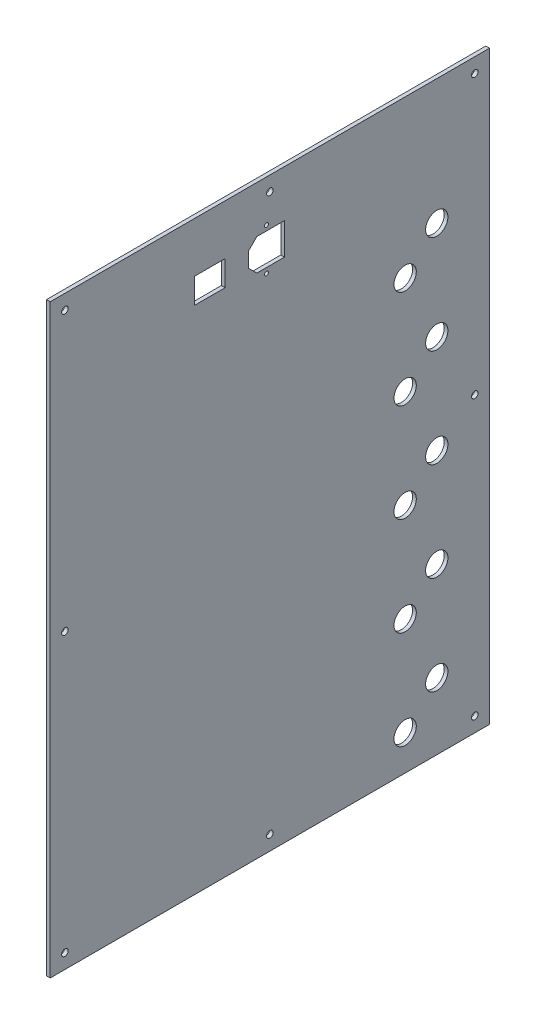
SolidWorks part; units mm, degrees
ref_plane "Front Plane" through (0, 0, 0) normal (1, 0, 0) x (0, 1, 0)
ref_plane "Top Plane" through (0, 0, 0) normal (0, 0, 1) x (0, 1, 0)
ref_plane "Right Plane" through (0, 0, 0) normal (0, 1, 0) x (-1, 0, 0)
sketch "Sketch1" plane through (0, 0, 0) normal (1, 0, 0) x (0, 1, 0)
  line L1 (-250, -187.5) -> (250, -187.5)
  line L2 (-250, -187.5) -> (-250, 187.5)
  line L3 (-250, 187.5) -> (250, 187.5)
  line L4 (250, -187.5) -> (250, 187.5)
  line L5 (-250, -187.5) -> (250, 187.5) construction
  line L6 (-250, 187.5) -> (250, -187.5) construction
  line L7 (237.5, -175) -> (-237.5, -175) construction
  line L8 (237.5, -175) -> (237.5, 175) construction
  line L9 (237.5, 175) -> (-237.5, 175) construction
  line L10 (-237.5, -175) -> (-237.5, 175) construction
  line L11 (237.5, -175) -> (-237.5, 175) construction
  line L12 (237.5, 175) -> (-237.5, -175) construction
  circle A0 centre (-237.5, 175) radius 2.8
  circle A1 centre (237.5, 175) radius 2.8
  circle A2 centre (237.5, -175) radius 2.8
  circle A3 centre (-237.5, -175) radius 2.8
  circle A4 centre (-237.5, 0) radius 2.8
  circle A5 centre (0, 175) radius 2.8
  circle A6 centre (237.5, 0) radius 2.8
  circle A7 centre (0, -175) radius 2.8
  point P0 (0, 0)
  point P6 (0, 0)
  dimension "D3" = 5.6
  dimension "D1" = 500
  dimension "D2" = 375
  dimension "D4" = 12.5
  dimension "D5" = 12.5
extrude "Boss-Extrude1" add sketch "Sketch1" along normal blind 3.175
sketch "Sketch2" plane through (3.175, 0, 0) normal (1, 0, 0) x (0, 1, 0)
  line L0 (-220, -115.5) -> (-250, -115.5) construction
  line L1 (-250, 187.5) -> (-250, -187.5) construction
  line L2 (-220, -115.5) -> (-193, -142.5) construction
  line L3 (-250, -187.5) -> (250, -187.5) construction
  circle A0 centre (-220, -115.5) radius 9.525
  circle A1 centre (-193, -142.5) radius 9.525
  circle A2 centre (-136, -115.5) radius 9.525
  circle A3 centre (-109, -142.5) radius 9.525
  circle A4 centre (-52, -115.5) radius 9.525
  circle A5 centre (-25, -142.5) radius 9.525
  circle A6 centre (32, -115.5) radius 9.525
  circle A7 centre (59, -142.5) radius 9.525
  circle A8 centre (116, -115.5) radius 9.525
  circle A9 centre (143, -142.5) radius 9.525
  point P4 (-140.2527, -115.5)
  dimension "D2" = 19.05
  dimension "D1" = 135
  dimension "D3" = 72
  dimension "D4" = 30
  dimension "D5" = 45
  dimension "D7" = 84
  dimension "D6" = 5
extrude "Cut-Extrude1" cut sketch "Sketch2" against normal through all
sketch "Sketch4" plane through (3.175, 0, 0) normal (1, 0, 0) x (0, 1, 0)
  line L0 (-250, -187.5) -> (250, -187.5) construction
  line L1 (210, -12.5) -> (183, -12.5)
  line L2 (210, -12.5) -> (210, 11.122)
  line L3 (202.888, 18.234) -> (190.112, 18.234)
  line L4 (183, -12.5) -> (183, 11.122)
  line L5 (210, -12.5) -> (183, 18.234) construction
  line L6 (210, 18.234) -> (183, -12.5) construction
  line L7 (250, -187.5) -> (250, 187.5) construction
  line L8 (190.112, 18.234) -> (183, 11.122)
  line L9 (210, 11.122) -> (202.888, 18.234)
  point P0 (196.5, 2.867)
  dimension "D1" = 27
  dimension "D2" = 175
  dimension "D3" = 40
  dimension "D4" = 30.734
extrude "Cut-Extrude2" cut sketch "Sketch4" against normal through all
sketch "Sketch5" plane through (3.175, 0, 0) normal (1, 0, 0) x (0, 1, 0)
  line L0 (196.5, 18.234) -> (196.5, -12.5) construction
  line L1 (202.888, 18.234) -> (190.112, 18.234) construction
  line L2 (183, -12.5) -> (210, -12.5) construction
  line L3 (178.593, 2.9) -> (214.407, 2.9) construction
  circle A0 centre (178.593, 2.9) radius 1.7
  circle A1 centre (214.407, 2.9) radius 1.7
  point P9 (196.5, 2.9)
  dimension "D1" = 3.4
  dimension "D2" = 35.814
  dimension "D3" = 15.4
extrude "Cut-Extrude3" cut sketch "Sketch5" against normal through all
sketch "Sketch6" plane through (3.175, 0, 0) normal (1, 0, 0) x (0, 1, 0)
  line L0 (196.5, 18.234) -> (196.5, 51.234) construction
  line L1 (202.888, 18.234) -> (190.112, 18.234) construction
  line L3 (207.25, 64.234) -> (185.75, 64.234)
  line L4 (207.25, 64.234) -> (207.25, 38.234)
  line L5 (207.25, 38.234) -> (185.75, 38.234)
  line L6 (185.75, 64.234) -> (185.75, 38.234)
  line L7 (207.25, 64.234) -> (185.75, 38.234) construction
  line L8 (207.25, 38.234) -> (185.75, 64.234) construction
  dimension "D1" = 21.5
  dimension "D2" = 26
  dimension "D3" = 20
extrude "Cut-Extrude4" cut sketch "Sketch6" against normal through all
